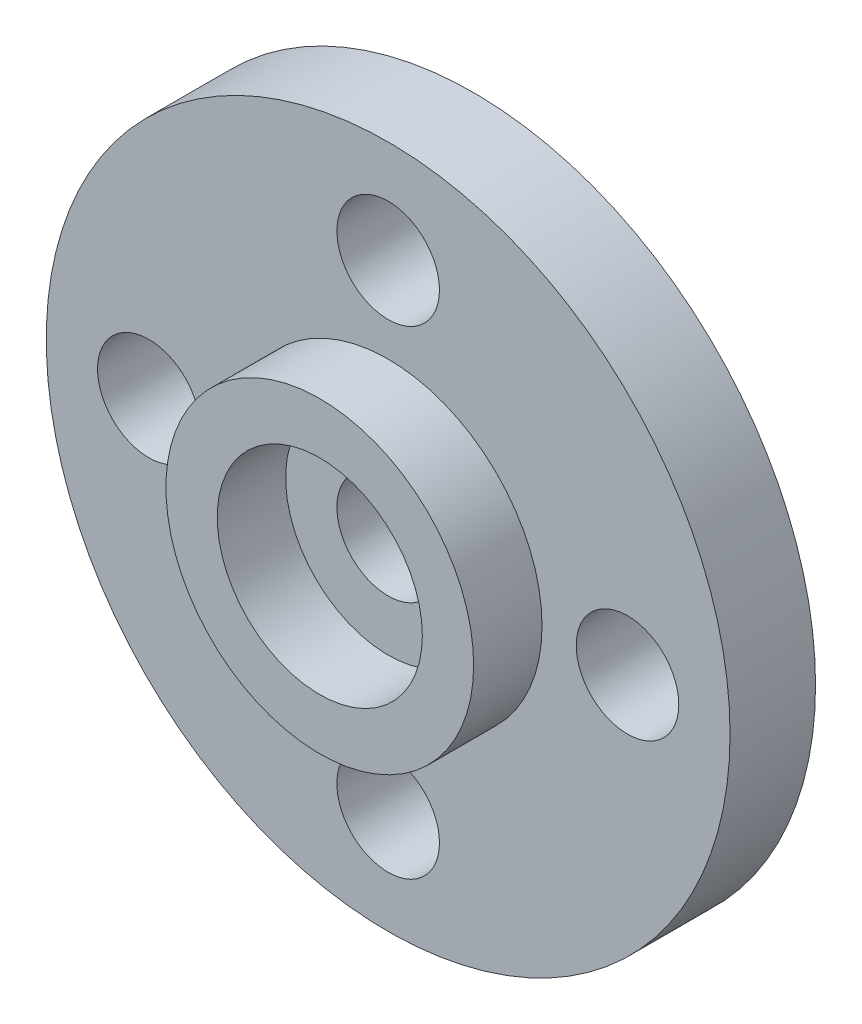
SolidWorks part; units mm, degrees
ref_plane "前视基准面" through (0, 0, 0) normal (0, 0, 1) x (1, 0, 0)
ref_plane "上视基准面" through (0, 0, 0) normal (0, 1, 0) x (1, 0, 0)
ref_plane "右视基准面" through (0, 0, 0) normal (1, 0, 0) x (0, 0, -1)
sketch "草图1" plane through (0, 0, 0) normal (0, 0, 1) x (1, 0, 0)
  circle A0 centre (0, 0) radius 10
  circle A1 centre (0, 0) radius 7 construction
  circle A2 centre (0, 7) radius 1.5
  circle A4 centre (7, 0) radius 1.5
  circle A6 centre (0, -7) radius 1.5
  circle A8 centre (-7, 0) radius 1.5
  circle A9 centre (0, 0) radius 7 [skipped]
  circle A10 centre (0, 0) radius 7 [skipped]
  circle A11 centre (0, 0) radius 7 [skipped]
  dimension "D1" = 20
  dimension "D2" = 14
  dimension "D3" = 3
  dimension "D4" = 4
extrude "凸台-拉伸1" add sketch "草图1" along normal blind 2.5
sketch "草图2" plane through (0, 0, 2.5) normal (0, 0, 1) x (1, 0, 0)
  circle A0 centre (0, 0) radius 3
  circle A1 centre (0, 0) radius 4.5
  dimension "D1" = 6
  dimension "D2" = 9
extrude "凸台-拉伸2" add sketch "草图2" along normal blind 2
sketch "草图3" plane through (0, 0, 2.5) normal (0, 0, 1) x (1, 0, 0)
  circle A0 centre (0, 0) radius 1.5
  dimension "D1" = 3
extrude "切除-拉伸1" cut sketch "草图3" against normal blind 3
